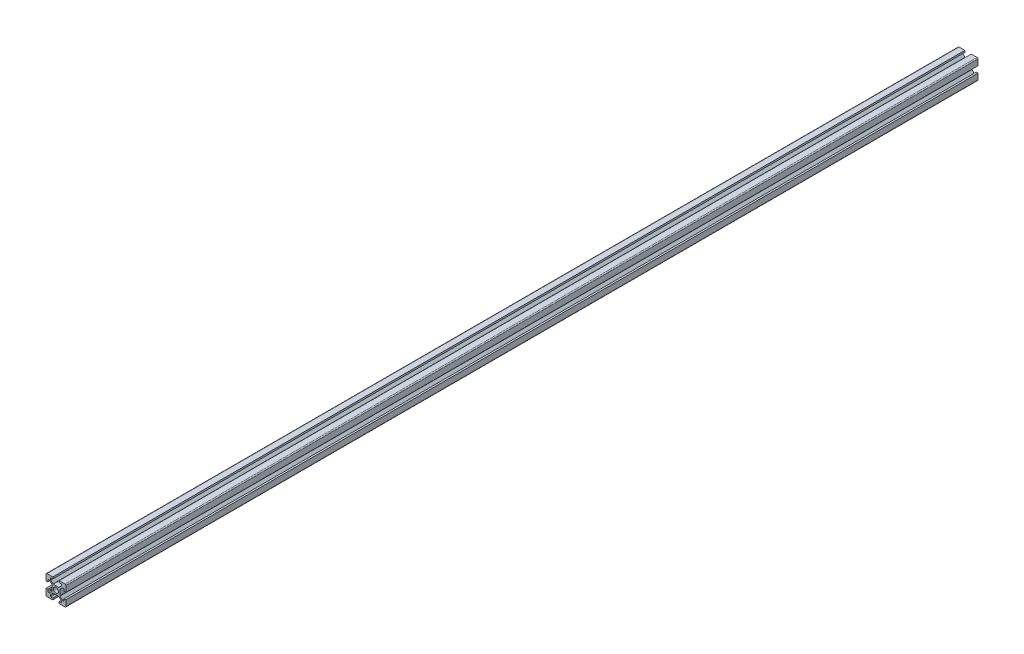
SolidWorks part; units mm, degrees
material "1060 Alloy"
ref_plane "Front Plane" through (0, 0, 0) normal (0, 0, 1) x (1, 0, 0)
ref_plane "Top Plane" through (0, 0, 0) normal (0, 1, 0) x (1, 0, 0)
ref_plane "Right Plane" through (0, 0, 0) normal (1, 0, 0) x (0, 0, -1)
sketch "Sketch1" plane through (0, 0, 0) normal (0, 0, 1) x (1, 0, 0)
  line L0 (20, 0) -> (-8.059, 28.059) construction
  line L1 (0, 0) -> (6.8, 0)
  line L2 (0, 0) -> (0, 6.8)
  line L3 (0, 20) -> (6.8, 20)
  line L4 (20, 0) -> (20, 6.8)
  line L5 (6.8, 20) -> (6.8, 18.2)
  line L6 (20, 20) -> (8.2322, 8.2322) construction
  line L7 (12.95, 6.1) -> (7.05, 6.1)
  line L8 (13.9, 7.05) -> (13.9, 12.95)
  line L9 (12.95, 13.9) -> (7.05, 13.9)
  line L10 (6.1, 7.05) -> (6.1, 12.95)
  line L11 (13.9, 6.1) -> (6.1, 13.9) construction
  line L12 (13.9, 13.9) -> (6.1, 6.1) construction
  line L13 (4.55, 16.4) -> (7.05, 13.9)
  line L14 (13.2, 18.2) -> (13.2, 20)
  line L15 (1.8, 6.8) -> (0, 6.8)
  line L16 (0, 13.2) -> (0, 20)
  line L17 (0, 13.2) -> (1.8, 13.2)
  line L18 (10, 10) -> (10, 13.9) construction
  line L19 (16.4, 4.55) -> (13.9, 7.05)
  line L20 (4.55, 16.4) -> (4.55, 18.2)
  line L21 (4.55, 18.2) -> (6.8, 18.2)
  line L22 (13.2, 18.2) -> (15.45, 18.2)
  line L23 (15.45, 18.2) -> (15.45, 16.4)
  line L24 (15.45, 16.4) -> (12.95, 13.9)
  line L25 (16.4, 4.55) -> (18.2, 4.55)
  line L26 (18.2, 4.55) -> (18.2, 6.8)
  line L27 (20, 6.8) -> (18.2, 6.8)
  line L28 (18.2, 13.2) -> (20, 13.2)
  line L29 (18.2, 13.2) -> (18.2, 15.45)
  line L30 (18.2, 15.45) -> (16.4, 15.45)
  line L31 (16.4, 15.45) -> (13.9, 12.95)
  line L32 (1.8, 4.55) -> (3.6, 4.55)
  line L33 (3.6, 15.45) -> (6.1, 12.95)
  line L34 (3.6, 15.45) -> (1.8, 15.45)
  line L35 (1.8, 15.45) -> (1.8, 13.2)
  line L36 (0, 13.2) -> (1.8, 13.2)
  line L37 (1.8, 6.8) -> (0, 6.8)
  line L38 (3.6, 4.55) -> (6.1, 7.05)
  line L39 (1.8, 6.8) -> (1.8, 4.55)
  line L40 (15.45, 3.6) -> (12.95, 6.1)
  line L41 (4.55, 3.6) -> (7.05, 6.1)
  line L42 (4.55, 1.8) -> (4.55, 3.6)
  line L43 (6.8, 1.8) -> (4.55, 1.8)
  line L44 (6.8, 1.8) -> (6.8, 0)
  line L45 (15.45, 3.6) -> (15.45, 1.8)
  line L46 (15.45, 1.8) -> (13.2, 1.8)
  line L47 (13.2, 0) -> (13.2, 1.8)
  line L48 (13.2, 20) -> (20, 20)
  line L49 (20, 13.2) -> (20, 20)
  line L50 (13.2, 0) -> (20, 0)
  line L51 (6.1, 6.1) -> (-5.5045, -5.5045) construction
  circle A0 centre (10, 10) radius 2.5
  point P25 (10, 16.4)
  point P39 (13.2, 19.1)
  point P46 (0.9, 6.8)
  dimension "D3" = 5
  dimension "D2" = 20
  dimension "D4" = 7.8
  dimension "D5" = 7.8
  dimension "D6" = 6.8
  dimension "D7" = 6.8
  dimension "D8" = 1.8
  dimension "D9" = 10.9
  dimension "D10" = 1.8
  dimension "D11" = 10.9
  dimension "D12" = 20
extrude "Boss-Extrude1" add sketch "Sketch1" along normal blind 914.4 contours L47 L50 L4 L27 L26 L25 L19 L8 L31 L30 L29 L28 L49 L48 L14 L22 L23 L24 L9 L13 L20 L21 L5 L3 L16 L17 L35 L34 L33 L10 L38 L32 L39 L15 L2 L1 L44 L43 L42 L41 L7 L40 L45 L46 A0
fillet "Fillet1" radius 1 4 edges at (20, 20, 457.2) (20, 0, 457.2) (0, 0, 457.2) (0, 20, 457.2)
fillet "Fillet2" radius 0.5 6 edges at (4.55, 18.2, 457.2) (4.55, 16.4, 457.2) (7.05, 13.9, 457.2) (15.45, 18.2, 457.2) (15.45, 16.4, 457.2) (12.95, 13.9, 457.2)
fillet "Fillet3" radius 0.5 6 edges at (18.2, 15.45, 457.2) (16.4, 15.45, 457.2) (13.9, 12.95, 457.2) (18.2, 4.55, 457.2) (13.9, 7.05, 457.2) (16.4, 4.55, 457.2)
fillet "Fillet4" radius 0.5 6 edges at (1.8, 15.45, 457.2) (3.6, 15.45, 457.2) (6.1, 12.95, 457.2) (3.6, 4.55, 457.2) (1.8, 4.55, 457.2) (6.1, 7.05, 457.2)
fillet "Fillet5" radius 0.5 6 edges at (7.05, 6.1, 457.2) (4.55, 3.6, 457.2) (4.55, 1.8, 457.2) (15.45, 1.8, 457.2) (15.45, 3.6, 457.2) (12.95, 6.1, 457.2)
